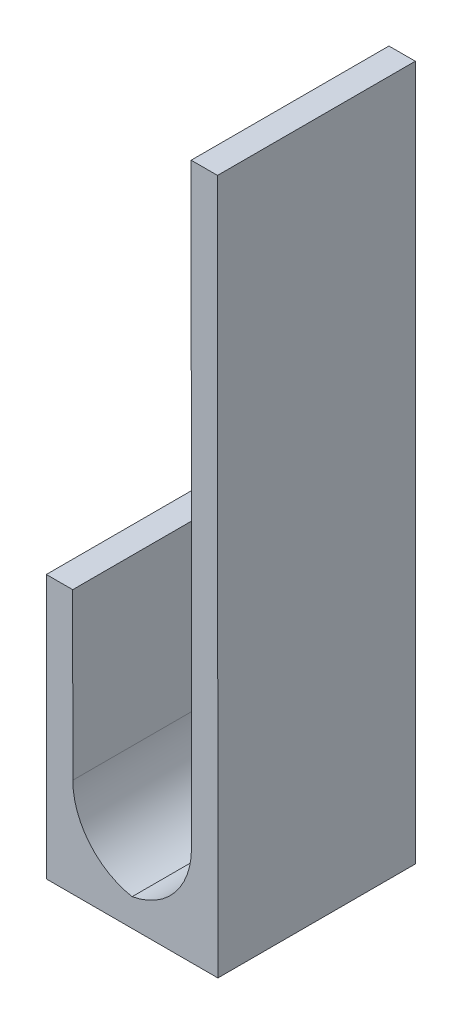
SolidWorks part; units mm, degrees
ref_plane "Front Plane" through (0, 0, 0) normal (0, 0, 1) x (1, 0, 0)
ref_plane "Top Plane" through (0, 0, 0) normal (0, 1, 0) x (1, 0, 0)
ref_plane "Right Plane" through (0, 0, 0) normal (1, 0, 0) x (0, 0, -1)
sketch "Sketch1" plane through (0, 0, 0) normal (0, 0, 1) x (1, 0, 0)
  line L0 (0, 0) -> (13.001, 0)
  line L3 (0, 2) -> (0, 0)
  line L4 (0, 2) -> (-0.0092, 20)
  line L5 (1.9908, 20.001) -> (-0.0092, 20)
  line L6 (12.9742, 52.7022) -> (13.001, 0)
  line L7 (1.9972, 7.4888) -> (1.9908, 20.001)
  line L8 (10.9742, 52.7011) -> (10.9972, 7.4944)
  line L9 (10.9742, 52.7011) -> (12.9742, 52.7022)
  line L10 (10.9795, 42.3729) -> (11, 1.9755) construction
  line L11 (2, 2.001) -> (1.9908, 20.001) construction
  line L12 (-0.0094, 20.3873) -> (12.9742, 52.7022) construction
  line L13 (1.9908, 20.001) -> (10.9795, 42.3729) construction
  line L14 (0, 2) -> (-0.0094, 20.3873) construction
  line L15 (10.9742, 52.7011) -> (11, 1.9755) construction
  line L21 (12.9742, 52.7022) -> (13, 1.9766) construction
  arc A3 (1.9972, 7.4888) -> (6.4972, 2.0903) centre (7.4888, 7.4916) ccw
  arc A4 (10.9972, 7.4944) -> (6.4972, 2.0903) centre (5.5056, 7.4916) cw
  point P16 (38.8406, 43.6796)
  point P18 (98.8294, 0.3783)
  point P30 (2, 2)
  dimension "D1" = 2
  dimension "D3" = 13
  dimension "D4" = 18
  dimension "D5" = 2
  dimension "D8" = 2
extrude "Boss-Extrude1" add sketch "Sketch1" along normal blind 15
